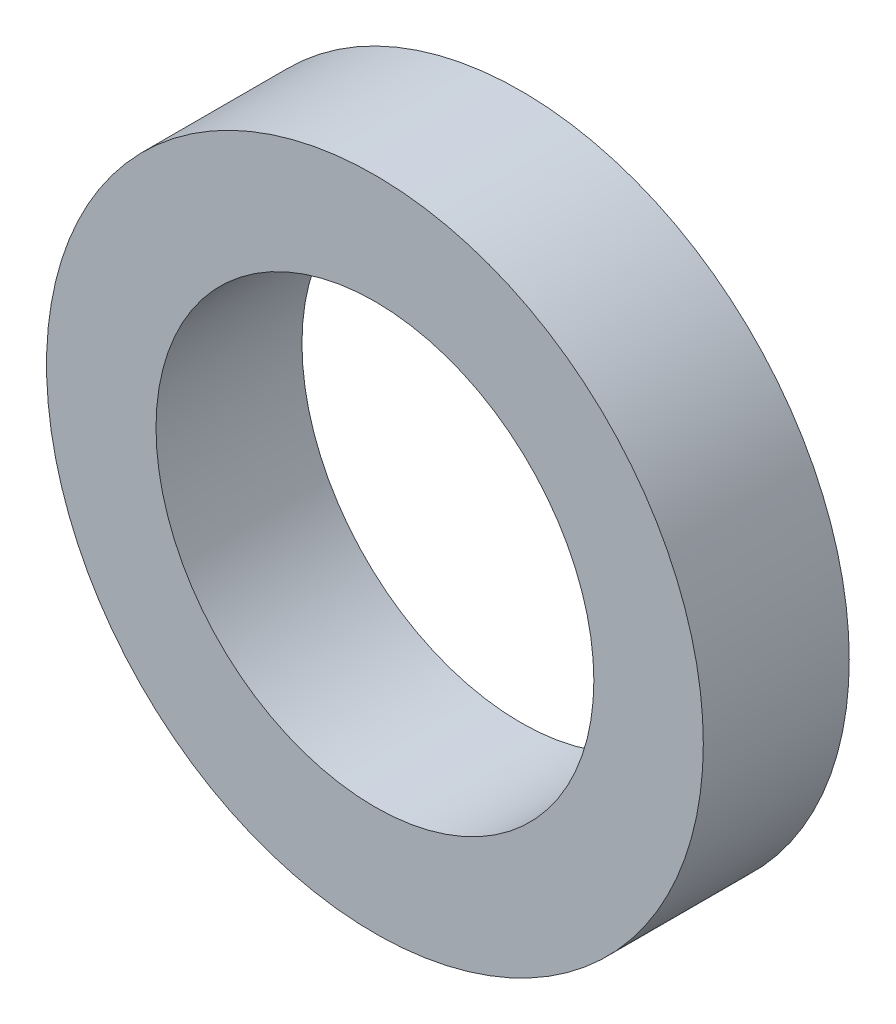
SolidWorks part; units mm, degrees
ref_plane "前视基准面" through (0, 0, 0) normal (0, 0, 1) x (1, 0, 0)
ref_plane "上视基准面" through (0, 0, 0) normal (0, 1, 0) x (1, 0, 0)
ref_plane "右视基准面" through (0, 0, 0) normal (1, 0, 0) x (0, 0, -1)
sketch "草图1" plane through (0, 0, 0) normal (0, 0, 1) x (1, 0, 0)
  circle A0 centre (0, 0) radius 9
  circle A1 centre (0, 0) radius 6
  dimension "D1" = 12
  dimension "D2" = 18
extrude "凸台-拉伸1" add sketch "草图1" along normal mid plane 4
